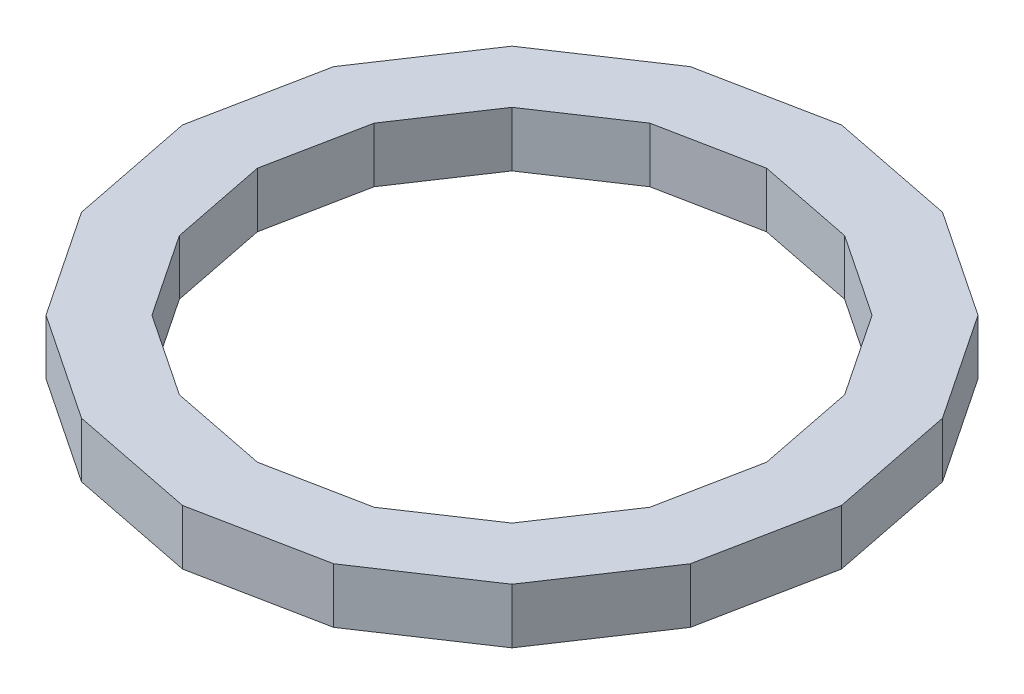
SolidWorks part; units mm, degrees
ref_plane "Front Plane" through (0, 0, 0) normal (0, 0, 1) x (1, 0, 0)
ref_plane "Top Plane" through (0, 0, 0) normal (0, 1, 0) x (1, 0, 0)
ref_plane "Right Plane" through (0, 0, 0) normal (1, 0, 0) x (0, 0, -1)
sketch "Sketch1" plane through (0, 0, 0) normal (0, 1, 0) x (1, 0, 0)
  line L1 (88.024, 0) -> (81.3236, 33.6853)
  line L2 (81.3236, 33.6853) -> (62.2424, 62.2424)
  line L3 (62.2424, 62.2424) -> (33.6853, 81.3236)
  line L4 (33.6853, 81.3236) -> (0, 88.024)
  line L5 (0, 88.024) -> (-33.6853, 81.3236)
  line L6 (-33.6853, 81.3236) -> (-62.2424, 62.2424)
  line L7 (-62.2424, 62.2424) -> (-81.3236, 33.6853)
  line L8 (-81.3236, 33.6853) -> (-88.024, 0)
  line L9 (-88.024, 0) -> (-81.3236, -33.6853)
  line L10 (-81.3236, -33.6853) -> (-62.2424, -62.2424)
  line L11 (-62.2424, -62.2424) -> (-33.6853, -81.3236)
  line L12 (-33.6853, -81.3236) -> (0, -88.024)
  line L13 (0, -88.024) -> (33.6853, -81.3236)
  line L14 (33.6853, -81.3236) -> (62.2424, -62.2424)
  line L15 (62.2424, -62.2424) -> (81.3236, -33.6853)
  line L16 (81.3236, -33.6853) -> (88.024, 0)
  line L17 (113.9216, 0) -> (105.2498, 43.5959)
  line L18 (105.2498, 43.5959) -> (80.5547, 80.5547)
  line L19 (80.5547, 80.5547) -> (43.5959, 105.2498)
  line L20 (43.5959, 105.2498) -> (0, 113.9216)
  line L21 (0, 113.9216) -> (-43.5959, 105.2498)
  line L22 (-43.5959, 105.2498) -> (-80.5547, 80.5547)
  line L23 (-80.5547, 80.5547) -> (-105.2498, 43.5959)
  line L24 (-105.2498, 43.5959) -> (-113.9216, 0)
  line L25 (-113.9216, 0) -> (-105.2498, -43.5959)
  line L26 (-105.2498, -43.5959) -> (-80.5547, -80.5547)
  line L27 (-80.5547, -80.5547) -> (-43.5959, -105.2498)
  line L28 (-43.5959, -105.2498) -> (0, -113.9216)
  line L29 (0, -113.9216) -> (43.5959, -105.2498)
  line L30 (43.5959, -105.2498) -> (80.5547, -80.5547)
  line L31 (80.5547, -80.5547) -> (105.2498, -43.5959)
  line L32 (105.2498, -43.5959) -> (113.9216, 0)
  circle A1 centre (0, 0) radius 86.3326 construction
  circle A2 centre (0, 0) radius 111.7326 construction
  dimension "D1" = 25.4
  dimension "D2" = 44.45
extrude "Boss-Extrude1" add sketch "Sketch1" along normal blind 19.05
